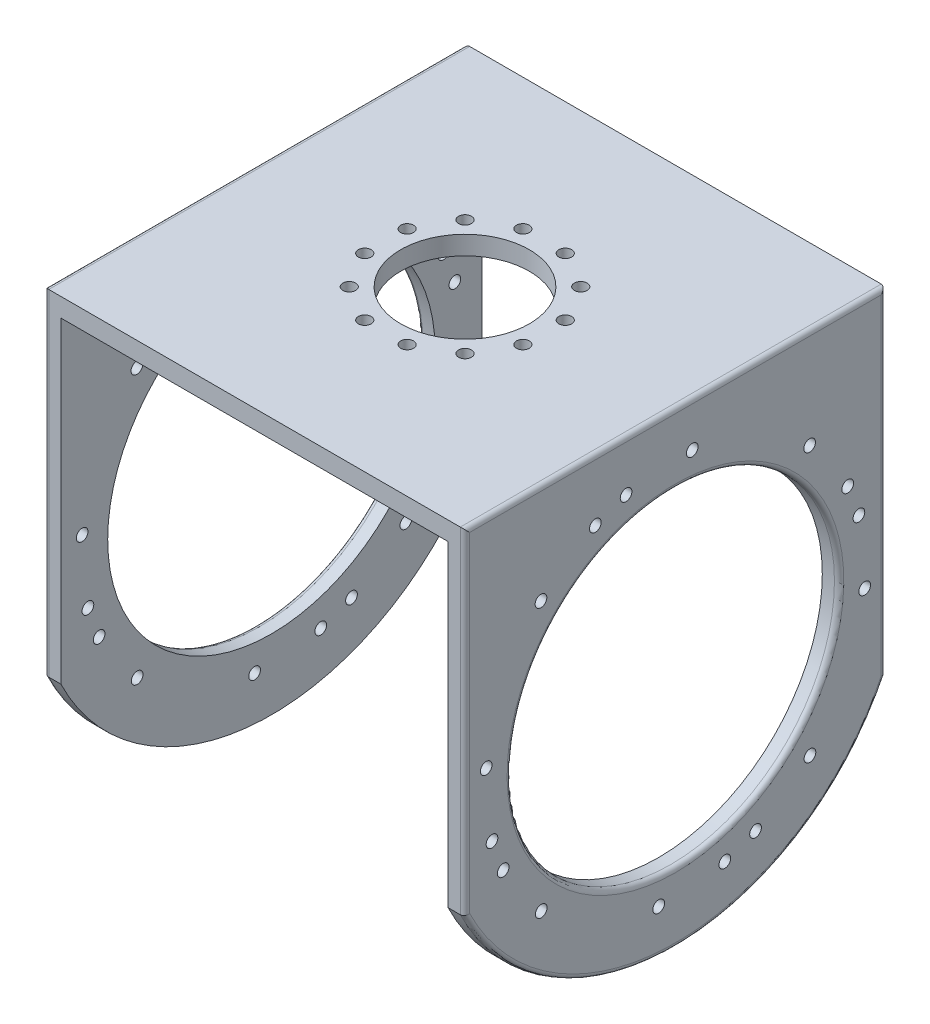
SolidWorks part; units mm, degrees
material "6061 合金"
ref_plane "前视基准面" through (0, 0, 0) normal (0, 0, 1) x (1, 0, 0)
ref_plane "上视基准面" through (0, 0, 0) normal (0, 1, 0) x (1, 0, 0)
ref_plane "右视基准面" through (0, 0, 0) normal (1, 0, 0) x (0, 0, -1)
other "Configuration Table"
sketch "草图1" plane through (0, 0, 0) normal (0, 0, 1) x (1, 0, 0)
  line L0 (0, 0) -> (0, 218.3382) construction
  line L1 (-90, 200) -> (90, 200)
  line L2 (90, 200) -> (90, 0)
  line L3 (90, 0) -> (82.8, 0)
  line L4 (82.8, 0) -> (82.8, 192)
  line L5 (82.8, 192) -> (-82.8, 192)
  line L6 (-82.8, 0) -> (-82.8, 192)
  line L7 (-90, 0) -> (-82.8, 0)
  line L8 (-90, 200) -> (-90, 0)
  point P11 (0, 192)
  point P14 (0, 200)
  dimension "D1" = 8
  dimension "D2" = 7.2
  dimension "D3" = 200
  dimension "D4" = 90
extrude "凸台-拉伸1" add sketch "草图1" along normal blind 180
sketch "草图2" plane through (0, 200, 0) normal (0, 1, 0) x (1, 0, 0)
  line L0 (-107.1953, -90) -> (124.7074, -90) construction
  line L1 (0, 14.5236) -> (0, -191.0225) construction
  line L2 (90, 0) -> (-90, 0) construction
  line L3 (90, -180) -> (-90, -180) construction
  circle A0 centre (0, -90) radius 27.5
  dimension "D1" = 55
extrude "切除-拉伸1" cut sketch "草图2" against normal blind 180
sketch "草图3" plane through (90, 0, 0) normal (1, 0, 0) x (0, 0, -1)
  line L0 (-202.0275, 100) -> (22.0275, 100) construction
  line L1 (-90, 182.9754) -> (-90, -6.0566) construction
  line L2 (-180, 0) -> (0, 0) construction
  line L3 (-180, 200) -> (0, 200) construction
  line L4 (0, 0) -> (0, 200) construction
  line L5 (-180, 0) -> (-180, 200) construction
  circle A0 centre (-90, 100) radius 70
  dimension "D1" = 140
extrude "切除-拉伸2" cut sketch "草图3" against normal blind 217 contours A0
sketch "草图4" plane through (0, 0, 0) normal (1, 0, 0) x (0, 0, -1)
  line L0 (-90, 200) -> (-90, 143.0513) construction
  line L1 (-62.5, 200) -> (-117.5, 200) construction
  line L2 (-70, 430) -> (60, 66.6573)
  line L3 (60, 66.6573) -> (-90, 66.6573) construction
  line L4 (-90, 66.6573) -> (-90, 700) construction
  line L5 (-70, 700) -> (60, 700)
  line L6 (60, 700) -> (60, 66.6573)
  line L7 (-70, 700) -> (-70, 430)
  circle A0 centre (-90, 100) radius 70 construction
  dimension "D1" = 500
  dimension "D2" = 130
  dimension "D3" = 150
  dimension "D4" = 230
  dimension "D5" = 20
revolve "切除-旋转6" [suppressed] cut sketch "草图4" angle 360 about L4
sketch "草图6" [suppressed] plane through (0, 0, 0) normal (1, 0, 0) x (0, 0, -1)
  line L0 (15.1538, 192) -> (60, 66.6573)
  line L1 (-25.1812, 192) -> (0, 192) construction
  line L2 (60, 66.6573) -> (-90, 66.6573) construction
  line L3 (60, 66.6573) -> (51.5034, 66.6573)
  line L4 (51.5034, 66.6573) -> (6.6571, 192)
  line L5 (-70, 430) -> (60, 66.6573) construction
  line L6 (6.6571, 192) -> (15.1538, 192)
  line L7 (-90, 66.6573) -> (-90, 200) construction
  dimension "D1" = 8
revolve "旋转1" [suppressed] add sketch "草图6" angle 360 about L7
sketch "草图7" [suppressed] plane through (0, 0, 0) normal (0, 0, 1) x (1, 0, 0)
  line L0 (90, 0) -> (90, 200)
  line L1 (90, 200) -> (162.5084, 200)
  line L2 (162.5084, 200) -> (162.5084, -21.519)
  line L3 (162.5084, -21.519) -> (-191.6551, -21.519)
  line L4 (-191.6551, -21.519) -> (-191.6551, 200)
  line L5 (-191.6551, 200) -> (-90, 200)
  line L6 (-90, 200) -> (-90, 0)
  line L7 (-90, 0) -> (-82.8, 0)
  line L10 (-35.2505, 192) -> (35.2505, 192)
  line L12 (82.8, 0) -> (90, 0)
  line L14 (35.2505, 192) -> (-35.2505, 192) construction
  line L15 (82.8, 0) -> (82.8, 120.3462)
  line L16 (82.8, 120.3462) -> (35.2505, 192)
  line L17 (-82.8, 0) -> (-82.8, 120.3462)
  line L18 (-82.8, 120.3462) -> (-35.2505, 192)
  line L19 (0, 0) -> (0, 120.3462) construction
  line L21 (35.2505, 192) -> (82.8, 192) construction
  line L22 (-82.8, 0) -> (-82.8, 120.3462) construction
  line L23 (-141.5034, 66.6573) -> (141.5034, 66.6573) construction
  line L24 (-35.2505, 192) -> (35.2505, 192) construction
  dimension "D1" = 53.6889
  dimension "D2" = 35.2505
extrude "切除-拉伸3" [suppressed] cut sketch "草图7" against normal through all both and the other way through all
sketch "草图8" [suppressed] plane through (-90, 0, 0) normal (-1, 0, 0) x (0, 0, 1)
  line L0 (0, 0) -> (0, 200)
  line L1 (0, 200) -> (180, 200)
  line L2 (180, 200) -> (180, 0)
  line L3 (180, 106.4129) -> (180, 0) construction
  line L4 (180, 0) -> (231.7354, 0)
  line L5 (231.7354, 0) -> (231.7354, 213.4055)
  line L6 (231.7354, 213.4055) -> (-43.5189, 213.4055)
  line L7 (-43.5189, 213.4055) -> (-43.5189, 0)
  line L8 (-43.5189, 0) -> (0, 0)
extrude "切除-拉伸4" [suppressed] cut sketch "草图8" against normal through all both
sketch "草图9" plane through (90, 0, 0) normal (1, 0, 0) x (0, 0, -1)
  line L3 (0, 56.411) -> (0, 0)
  line L4 (-180, 200) -> (-180, 0)
  line L5 (-180, 0) -> (0, 0)
  line L6 (0, 0) -> (0, 200)
  line L7 (0, 200) -> (-180, 200)
  line L8 (-180, 56.411) -> (-180, 0)
  line L9 (-180, 0) -> (0, 0)
  line L11 (0, 200) -> (-180, 200) construction
  circle A0 centre (-90, 100) radius 70 construction
  circle A1 centre (-90, 100) radius 70 construction
  arc A3 (-180, 56.411) -> (0, 56.411) centre (-90, 100) ccw
  line M11 (-180, 200) -> (-180, 0)
  line M12 (-180, 0) -> (0, 0)
  line M13 (0, 0) -> (0, 200)
  dimension "D1" = 0
extrude "切除-拉伸5" cut sketch "草图9" against normal through all both contours A3 L9 M13 | A3 M11 M12
fillet "圆角1" [suppressed] radius 2
fillet "圆角2" radius 2 10 edges at (90, 200, 90) (90, 128.2055, 0) (90, 0, 90) (90, 128.2055, 180) (90, 170, 90) (-90, 128.2055, 0) (-90, 200, 90) (-90, 128.2055, 180) (-90, 0, 90) (-90, 170, 90)
sketch "草图10" plane through (90, 0, 0) normal (1, 0, 0) x (0, 0, -1)
  arc A0 (-173.1989, 108.2258) -> (-168.6673, 106.1128) centre (-170.9331, 107.1693) ccw construction
  arc A1 (-170.7244, 79.9423) -> (-166.1928, 77.8292) centre (-168.4586, 78.8857) ccw construction
  arc A2 (-165.9405, 66.7988) -> (-161.409, 64.6857) centre (-163.6748, 65.7423) ccw construction
  arc A3 (-149.6558, 43.5418) -> (-145.1242, 41.4287) centre (-147.39, 42.4852) ccw construction
  arc A4 (-99.4351, 20.1235) -> (-94.9035, 18.0104) centre (-97.1693, 19.0669) ccw construction
  arc A5 (-71.1515, 22.598) -> (-66.62, 20.4849) centre (-68.8857, 21.5414) ccw construction
  arc A6 (-58.008, 27.3818) -> (-53.4765, 25.2687) centre (-55.7423, 26.3252) ccw construction
  arc A7 (-34.751, 43.6665) -> (-30.2194, 41.5535) centre (-32.4852, 42.61) ccw construction
  arc A8 (-11.3327, 93.8872) -> (-6.8011, 91.7742) centre (-9.0669, 92.8307) ccw construction
  arc A9 (-13.8072, 122.1708) -> (-9.2756, 120.0577) centre (-11.5414, 121.1143) ccw construction
  arc A10 (-18.591, 135.3143) -> (-14.0595, 133.2012) centre (-16.3252, 134.2577) ccw construction
  arc A11 (-34.8758, 158.5713) -> (-30.3442, 156.4582) centre (-32.61, 157.5148) ccw construction
  arc A12 (-85.0965, 181.9896) -> (-80.5649, 179.8765) centre (-82.8307, 180.9331) ccw construction
  arc A13 (-108.8485, 177.402) -> (-113.38, 179.5151) centre (-111.1143, 178.4586) ccw construction
  arc A14 (-121.992, 172.6182) -> (-126.5235, 174.7313) centre (-124.2577, 173.6748) ccw construction
  arc A15 (-145.249, 156.3335) -> (-149.7806, 158.4465) centre (-147.5148, 157.39) ccw construction
  arc A16 (-173.1989, 108.2258) -> (-168.6673, 106.1128) centre (-170.9331, 107.1693) ccw construction
  arc A17 (-170.7244, 79.9423) -> (-166.1928, 77.8292) centre (-168.4586, 78.8857) ccw construction
  arc A18 (-165.9405, 66.7988) -> (-161.409, 64.6857) centre (-163.6748, 65.7423) ccw construction
  arc A19 (-149.6558, 43.5418) -> (-145.1242, 41.4287) centre (-147.39, 42.4852) ccw construction
  arc A20 (-99.4351, 20.1235) -> (-94.9035, 18.0104) centre (-97.1693, 19.0669) ccw construction
  arc A21 (-71.1515, 22.598) -> (-66.62, 20.4849) centre (-68.8857, 21.5414) ccw construction
  arc A22 (-58.008, 27.3818) -> (-53.4765, 25.2687) centre (-55.7423, 26.3252) ccw construction
  arc A23 (-34.751, 43.6665) -> (-30.2194, 41.5535) centre (-32.4852, 42.61) ccw construction
  arc A24 (-11.3327, 93.8872) -> (-6.8011, 91.7742) centre (-9.0669, 92.8307) ccw construction
  arc A25 (-13.8072, 122.1708) -> (-9.2756, 120.0577) centre (-11.5414, 121.1143) ccw construction
  arc A26 (-18.591, 135.3143) -> (-14.0595, 133.2012) centre (-16.3252, 134.2577) ccw construction
  arc A27 (-34.8758, 158.5713) -> (-30.3442, 156.4582) centre (-32.61, 157.5148) ccw construction
  arc A28 (-85.0965, 181.9896) -> (-80.5649, 179.8765) centre (-82.8307, 180.9331) ccw construction
  arc A29 (-108.8485, 177.402) -> (-113.38, 179.5151) centre (-111.1143, 178.4586) ccw construction
  arc A30 (-121.992, 172.6182) -> (-126.5235, 174.7313) centre (-124.2577, 173.6748) ccw construction
  arc A31 (-145.249, 156.3335) -> (-149.7806, 158.4465) centre (-147.5148, 157.39) ccw construction
  circle A32 centre (-32.61, 157.5148) radius 2.5
  circle A33 centre (-16.3252, 134.2577) radius 2.5
  circle A34 centre (-11.5414, 121.1143) radius 2.5
  circle A35 centre (-9.0669, 92.8307) radius 2.5
  circle A36 centre (-32.4852, 42.61) radius 2.5
  circle A37 centre (-55.7423, 26.3252) radius 2.5
  circle A38 centre (-68.8857, 21.5414) radius 2.5
  circle A39 centre (-97.1693, 19.0669) radius 2.5
  circle A40 centre (-147.39, 42.4852) radius 2.5
  circle A41 centre (-163.6748, 65.7423) radius 2.5
  circle A42 centre (-168.4586, 78.8857) radius 2.5
  circle A43 centre (-170.9331, 107.1693) radius 2.5
  circle A44 centre (-147.5148, 157.39) radius 2.5
  circle A45 centre (-124.2577, 173.6748) radius 2.5
  circle A46 centre (-111.1143, 178.4586) radius 2.5
  circle A47 centre (-82.8307, 180.9331) radius 2.5
  dimension "D1" = 5
extrude "切除-拉伸6" cut sketch "草图10" against normal through all both and the other way through all
sketch "草图11" plane through (0, 192, 0) normal (0, -1, 0) x (1, 0, 0)
  line L0 (0, 90) -> (0, 156.7057) construction
  line L1 (0, 90) -> (16.0765, 149.9982) construction
  circle A0 centre (9.0587, 123.8074) radius 2.75
  circle A1 centre (24.7487, 114.7487) radius 2.75
  circle A2 centre (33.8074, 99.0587) radius 2.75
  circle A3 centre (33.8074, 80.9413) radius 2.75
  circle A4 centre (24.7487, 65.2513) radius 2.75
  circle A5 centre (9.0587, 56.1926) radius 2.75
  circle A6 centre (-9.0587, 56.1926) radius 2.75
  circle A7 centre (-24.7487, 65.2513) radius 2.75
  circle A8 centre (-33.8074, 80.9413) radius 2.75
  circle A9 centre (-33.8074, 99.0587) radius 2.75
  circle A10 centre (-24.7487, 114.7487) radius 2.75
  circle A11 centre (-9.0587, 123.8074) radius 2.75
  point P31 (0, 90)
  dimension "D1" = 5.5
  dimension "D2" = 35
  dimension "D3" = 15
  dimension "D4" = 12
extrude "切除-拉伸7" cut sketch "草图11" against normal blind 29
